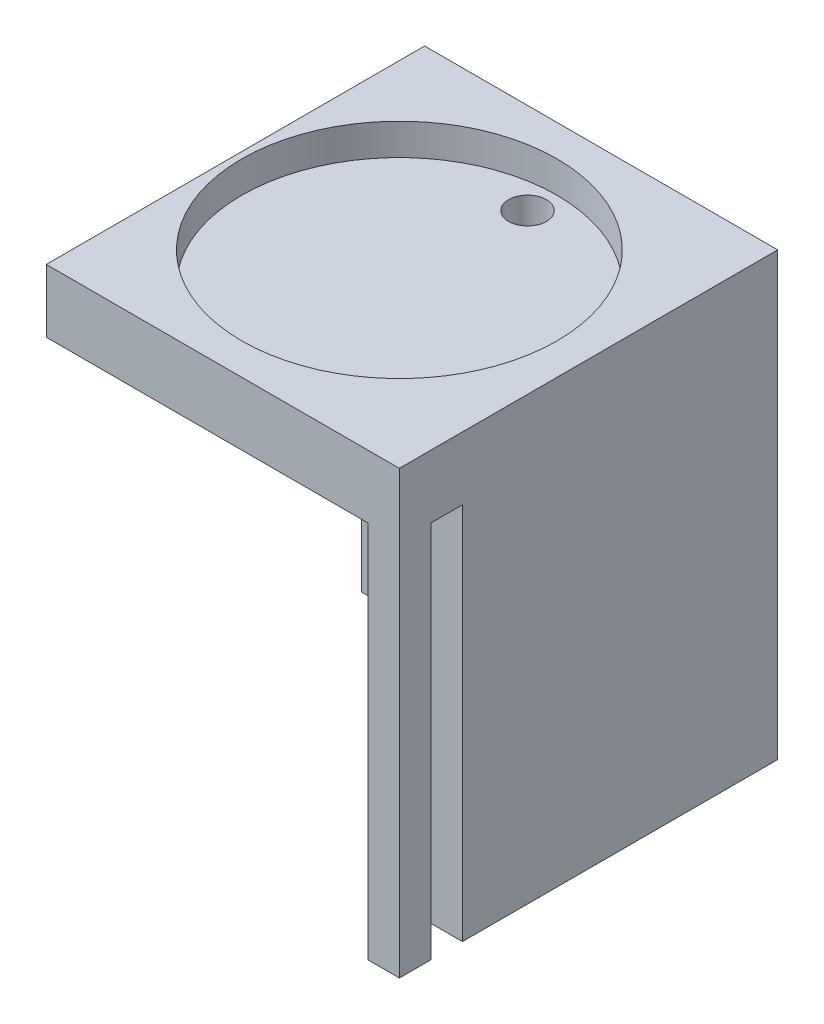
SolidWorks part; units mm, degrees
ref_plane "정면" through (0, 0, 0) normal (0, 0, 1) x (1, 0, 0)
ref_plane "윗면" through (0, 0, 0) normal (0, 1, 0) x (1, 0, 0)
ref_plane "우측면" through (0, 0, 0) normal (1, 0, 0) x (0, 0, -1)
sketch "Sketch1" plane through (0, 0, 0) normal (0, 1, 0) x (1, 0, 0)
  line L1 (0, 0) -> (670, 0)
  line L2 (0, 0) -> (0, 120)
  line L3 (0, 120) -> (670, 120)
  line L4 (670, 0) -> (670, 120)
  dimension "700" = 670
  dimension "D2" = 120
extrude "Boss-Extrude1" add sketch "Sketch1" along normal blind 530
sketch "Sketch2" plane through (0, 0, 0) normal (0, 0, 1) x (1, 0, 0)
  line L0 (0, 530) -> (0, 0) construction
  line L1 (10, 280) -> (110, 280)
  line L2 (10, 280) -> (10, 480)
  line L3 (10, 480) -> (110, 480)
  line L4 (110, 280) -> (110, 480)
  line L5 (0, 0) -> (670, 0) construction
  line L6 (120, 280) -> (120, 480)
  line L7 (120, 280) -> (220, 280)
  line L8 (220, 280) -> (220, 480)
  line L9 (120, 480) -> (220, 480)
  line L10 (230, 280) -> (230, 480)
  line L11 (230, 280) -> (330, 280)
  line L12 (330, 280) -> (330, 480)
  line L13 (230, 480) -> (330, 480)
  line L14 (340, 280) -> (340, 480)
  line L15 (340, 280) -> (440, 280)
  line L16 (440, 280) -> (440, 480)
  line L17 (340, 480) -> (440, 480)
  line L18 (450, 280) -> (450, 480)
  line L19 (450, 280) -> (550, 280)
  line L20 (550, 280) -> (550, 480)
  line L21 (450, 480) -> (550, 480)
  line L22 (560, 280) -> (560, 480)
  line L23 (560, 280) -> (660, 280)
  line L24 (660, 280) -> (660, 480)
  line L25 (560, 480) -> (660, 480)
  line L27 (10, 10) -> (660, 10)
  line L28 (10, 10) -> (10, 260)
  line L29 (10, 260) -> (660, 260)
  line L30 (660, 10) -> (660, 260)
  line L31 (0, 530) -> (670, 530) construction
  point P6 (10, 380)
  dimension "D1" = 100
  dimension "D2" = 200
  dimension "D3" = 10
  dimension "D4" = 50
  dimension "D6" = 10
  dimension "D7" = 20
  dimension "D5" = 6
extrude "Cut-Extrude1" cut sketch "Sketch2" against normal blind 100
sketch "Sketch3" plane through (0, 530, 0) normal (0, 1, 0) x (1, 0, 0)
  line L1 (670, 120) -> (0, 120) construction
  line L2 (0, 120) -> (0, 0) construction
  circle A0 centre (60, 60) radius 50
  circle A1 centre (170, 60) radius 50
  circle A2 centre (280, 60) radius 50
  circle A3 centre (390, 60) radius 50
  circle A4 centre (500, 60) radius 50
  circle A5 centre (610, 60) radius 50
  dimension "D1" = 100
  dimension "D2" = 10
  dimension "D3" = 10
  dimension "D4" = 6
extrude "Cut-Extrude2" cut sketch "Sketch3" against normal blind 260
hole_wizard "Ø12.0 (12) Diameter Hole2" positions "3DSketch1" profile "Sketch7" hole size "Ø12.0" standard "Ansi Metric"
sketch3d "3DSketch1"
  point P0 (59.7046, 270, -102.4117)
  point P2 (171.5567, 270, -102.6076)
  point P4 (280.8723, 270, -102.3969)
  point P6 (391.0687, 270, -102.7535)
  point P8 (500.7133, 270, -101.754)
  point P10 (609.5165, 270, -101.1227)
sketch "Sketch7" plane through (59.7046, 270, -102.4117) normal (1, 0, 0) x (0, 0, 1)
  line L0 (0, 0) -> (0, 33.6052)
  line L1 (0, 33.6052) -> (6, 30)
  line L2 (6, 30) -> (6, 0)
  line L5 (6, 0) -> (0, 0)
  line L10 (0, 33.6052) -> (-6, 30) construction
  line L11 (0, -6.35) -> (0, 107.95) construction
  dimension "구멍 지름" = 12
  dimension "구멍 깊이" = 30
  dimension "드릴 각도" = 118
sketch "Sketch8" plane through (0, 0, 0) normal (0, 0, 1) x (1, 0, 0)
  line L0 (660, 280) -> (660, 480) construction
  line L1 (10, 280) -> (660, 280)
  line L2 (10, 280) -> (10, 330)
  line L3 (10, 330) -> (660, 330)
  line L4 (660, 280) -> (660, 330)
  dimension "D1" = 50
extrude "Boss-Extrude2" add sketch "Sketch8" against normal blind 5
sketch "Sketch9" plane through (670, 0, 0) normal (1, 0, 0) x (0, 0, -1)
  line L0 (0, 530) -> (0, 0) construction
  line L1 (10, 10) -> (20, 10)
  line L2 (10, 10) -> (10, 260)
  line L3 (10, 260) -> (20, 260)
  line L4 (20, 10) -> (20, 260)
  line L5 (0, 0) -> (120, 0) construction
  dimension "D1" = 10
  dimension "D2" = 10
  dimension "D3" = 10
  dimension "D4" = 250
extrude "Cut-Extrude3" cut sketch "Sketch9" against normal blind 717
sketch "Sketch10" plane through (0, 10, 0) normal (0, 1, 0) x (1, 0, 0)
  line L0 (670, 120) -> (0, 120) construction
  line L1 (365, 61.9436) -> (350, 87.9243)
  line L2 (350, 87.9243) -> (320, 87.9243)
  line L3 (320, 87.9243) -> (305, 61.9436)
  line L4 (305, 61.9436) -> (320, 35.9628)
  line L5 (320, 35.9628) -> (350, 35.9628)
  line L6 (350, 35.9628) -> (365, 61.9436)
  line L7 (0, 120) -> (0, 0) construction
  circle A0 centre (335, 61.9436) radius 25.9808 construction
  dimension "D1" = 60
  dimension "D2" = 305
extrude "Cut-Extrude4" cut sketch "Sketch10" against normal blind 5
sketch "Sketch11" plane through (0, 0, -100) normal (0, 0, 1) x (1, 0, 0)
  line L0 (10, 10) -> (660, 10) construction
  line L1 (250, 10) -> (260, 10)
  line L2 (250, 10) -> (250, 110)
  line L3 (250, 110) -> (260, 110)
  line L4 (260, 10) -> (260, 110)
  line L5 (660, 10) -> (660, 260) construction
  line L6 (410, 10) -> (420, 10)
  line L7 (410, 10) -> (410, 110)
  line L8 (410, 110) -> (420, 110)
  line L9 (420, 10) -> (420, 110)
  line L10 (25, 198.4569) -> (325, 145.5588)
  line L11 (325, 145.5588) -> (325, 122.0178)
  line L12 (325, 122.0178) -> (345, 122.0178)
  line L13 (345, 122.0178) -> (345, 145.5588)
  line L14 (345, 145.5588) -> (645, 198.4569)
  line L15 (645, 198.4569) -> (25, 198.4569)
  point P18 (345, 133.7883)
  dimension "D1" = 10
  dimension "D2" = 10
  dimension "D3" = 100
  dimension "D4" = 100
  dimension "D5" = 150
  dimension "D6" = 240
  dimension "D7" = 20
  dimension "D8" = 65
  dimension "D9" = 100
  dimension "D10" = 620
  dimension "D11" = 100
extrude "Boss-Extrude3" add sketch "Sketch11" along normal blind 78 separate body
sketch "Sketch12" plane through (0, 0, -100) normal (0, 0, 1) x (1, 0, 0)
  line L0 (660, 260) -> (10, 260) construction
  line L1 (75.1986, 260) -> (95.1986, 260)
  line L2 (75.1986, 260) -> (75.1986, 230)
  line L3 (75.1986, 230) -> (95.1986, 230)
  line L4 (95.1986, 260) -> (95.1986, 230)
  line L5 (65.1986, 260) -> (65.1986, 240) construction
  line L6 (185.1986, 260) -> (185.1986, 230)
  line L7 (185.1986, 260) -> (205.1986, 260)
  line L8 (205.1986, 260) -> (205.1986, 230)
  line L9 (185.1986, 230) -> (205.1986, 230)
  line L10 (295.1986, 260) -> (295.1986, 230)
  line L11 (295.1986, 260) -> (315.1986, 260)
  line L12 (315.1986, 260) -> (315.1986, 230)
  line L13 (295.1986, 230) -> (315.1986, 230)
  line L14 (405.1986, 260) -> (405.1986, 230)
  line L15 (405.1986, 260) -> (425.1986, 260)
  line L16 (425.1986, 260) -> (425.1986, 230)
  line L17 (405.1986, 230) -> (425.1986, 230)
  line L18 (515.1986, 260) -> (515.1986, 230)
  line L19 (515.1986, 260) -> (535.1986, 260)
  line L20 (535.1986, 260) -> (535.1986, 230)
  line L21 (515.1986, 230) -> (535.1986, 230)
  line L22 (625.1986, 260) -> (625.1986, 230)
  line L23 (625.1986, 260) -> (645.1986, 260)
  line L24 (645.1986, 260) -> (645.1986, 230)
  line L25 (625.1986, 230) -> (645.1986, 230)
  dimension "D1" = 20
  dimension "D2" = 30
  dimension "D3" = 10
  dimension "D4" = 6
extrude "Cut-Extrude5" cut sketch "Sketch12" against normal blind 80
sketch "Sketch15" plane through (345, 0, 0) normal (1, 0, 0) x (0, 0, -1)
  line L0 (20, 10) -> (20, 260) construction
  line L1 (20, 121.4638) -> (50, 121.4638)
  line L2 (20, 121.4638) -> (20, 145)
  line L3 (20, 145) -> (50, 145)
  line L4 (50, 121.4638) -> (50, 145)
  line L5 (120, 530) -> (120, 0) construction
  line L6 (100, 116.0134) -> (70, 116.0134)
  line L7 (100, 116.0134) -> (100, 145)
  line L8 (100, 145) -> (70, 145)
  line L9 (70, 116.0134) -> (70, 145)
  line L10 (20, 260) -> (10, 260) construction
  dimension "D1" = 20
  dimension "D2" = 20
  dimension "D3" = 115
  dimension "D4" = 30
extrude "Cut-Extrude7" cut sketch "Sketch15" against normal blind 35
shell "Shell1" thickness 3
sketch "Sketch16" plane through (0, 122.0178, 0) normal (0, -1, 0) x (1, 0, 0)
  line L0 (345, -50) -> (325, -50) construction
  line L1 (328, -53) -> (342, -53)
  line L2 (328, -53) -> (328, -67)
  line L3 (328, -67) -> (342, -67)
  line L4 (342, -53) -> (342, -67)
  line L5 (325, -50) -> (325, -70) construction
  line L6 (345, -50) -> (345, -70) construction
  line L7 (325, -70) -> (345, -70) construction
  dimension "D1" = 3
  dimension "D2" = 3
  dimension "D3" = 3
  dimension "D4" = 3
extrude "Cut-Extrude8" cut sketch "Sketch16" against normal blind 35
sketch "Sketch17" plane through (0, 0, 0) normal (0, 0, 1) x (1, 0, 0)
  text T0 "<b>DIFF_USER</b>" font "Britannic Bold" height in points 72
extrude "Boss-Extrude4" add sketch "Sketch17" along normal blind 5
sketch "Sketch18" plane through (0, 0, 0) normal (0, 0, 1) x (1, 0, 0)
  line L0 (0, 530) -> (670, 530) construction
  line L1 (0, 530) -> (670, 530)
  line L2 (0, 530) -> (0, 280)
  line L3 (0, 280) -> (670, 280)
  line L4 (670, 530) -> (670, 280)
  line L5 (670, 530) -> (670, 0) construction
  line L6 (0, 0) -> (670, 0) construction
  dimension "D1" = 280
extrude "Cut-Extrude10" cut sketch "Sketch18" against normal through all both and the other way through all
delete or keep bodies "Body-Delete/Keep 1" type delete bodies bodies 109 115 112
sketch "Sketch19" plane through (0, 0, -120) normal (0, 0, -1) x (-1, 0, 0)
  line L0 (0, 280) -> (-670, 280) construction
  line L1 (0, 0) -> (-558, 0)
  line L2 (0, 0) -> (0, 280)
  line L3 (0, 280) -> (-558, 280)
  line L4 (-558, 0) -> (-558, 280)
  line L5 (-670, 280) -> (-670, 0) construction
  dimension "D1" = 112
extrude "Cut-Extrude12" cut sketch "Sketch19" against normal through all both and the other way through all
sketch "Sketch20" plane through (660, 0, 0) normal (-1, 0, 0) x (0, 0, 1)
  line L0 (0, 10) -> (0, 260) construction
  line L1 (-120, 0) -> (0, 0)
  line L2 (-120, 0) -> (-120, 140)
  line L3 (-120, 140) -> (0, 140)
  line L4 (0, 0) -> (0, 140)
  dimension "D1" = 140
extrude "Cut-Extrude13" cut sketch "Sketch20" against normal through all both and the other way through all
